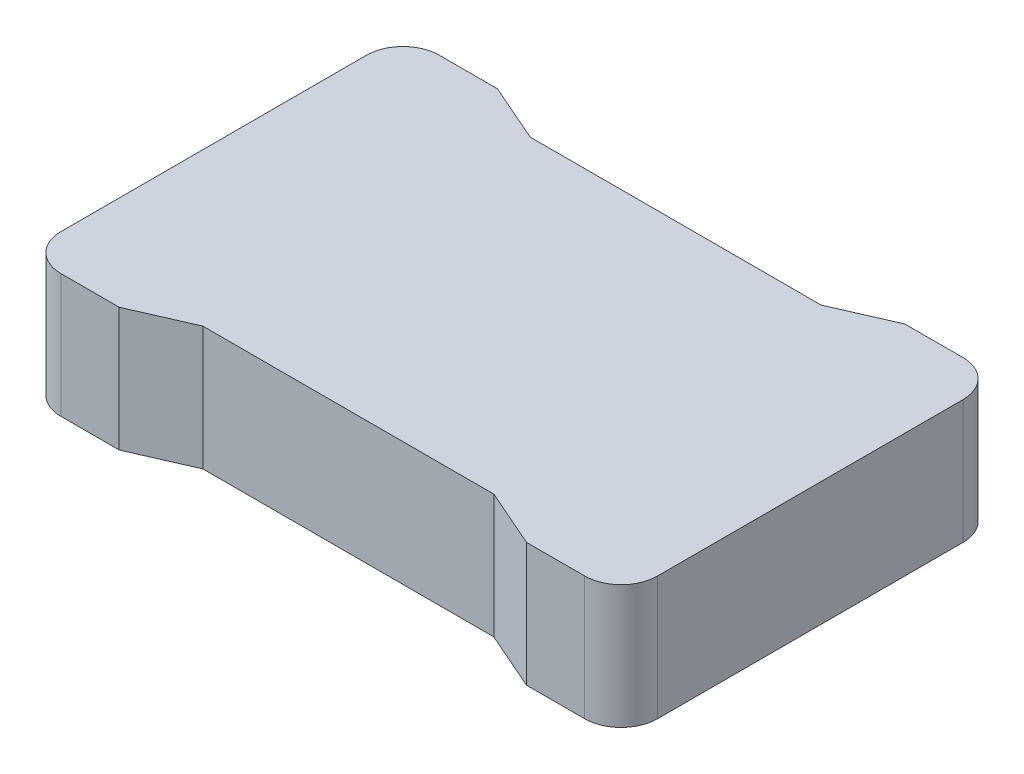
SolidWorks part; units mm, degrees
ref_plane "前基準面" through (0, 0, 0) normal (0, 0, 1) x (1, 0, 0)
ref_plane "上基準面" through (0, 0, 0) normal (0, 1, 0) x (1, 0, 0)
ref_plane "右基準面" through (0, 0, 0) normal (1, 0, 0) x (0, 0, -1)
sketch "草圖1" plane through (0, 0, 0) normal (0, 1, 0) x (1, 0, 0)
  line L0 (28, 26) -> (36, 26)
  line L1 (-36, -26) -> (-28, -26)
  line L2 (-41, -21) -> (-41, 21)
  line L3 (-36, 26) -> (-28, 26)
  line L4 (41, -21) -> (41, 21)
  line L5 (-41, -26) -> (41, 26) construction
  line L6 (-41, 26) -> (41, -26) construction
  line L7 (-20, -22.5) -> (20, -22.5)
  line L8 (-20, -22.5) -> (-20, 22.5) construction
  line L9 (-20, 22.5) -> (20, 22.5)
  line L10 (20, -22.5) -> (20, 22.5) construction
  line L11 (-20, -22.5) -> (20, 22.5) construction
  line L12 (-20, 22.5) -> (20, -22.5) construction
  line L13 (-28, -26) -> (28, -26) construction
  line L14 (-28, -26) -> (-28, 26) construction
  line L15 (-28, 26) -> (28, 26) construction
  line L16 (28, -26) -> (28, 26) construction
  line L17 (-28, -26) -> (28, 26) construction
  line L18 (-28, 26) -> (28, -26) construction
  line L19 (28, -26) -> (36, -26)
  line L20 (-28, 26) -> (-20, 22.5)
  line L21 (20, 22.5) -> (28, 26)
  line L22 (28, -26) -> (20, -22.5)
  line L23 (-20, -22.5) -> (-28, -26)
  arc A0 (36, -26) -> (41, -21) centre (36, -21) ccw
  arc A1 (36, 26) -> (41, 21) centre (36, 21) cw
  arc A2 (-36, -26) -> (-41, -21) centre (-36, -21) cw
  arc A3 (-41, 21) -> (-36, 26) centre (-36, 21) cw
  point P0 (0, 0)
  point P6 (0, 0)
  point P11 (0, 0)
  point P16 (-29.4708, 26)
  point P29 (0, 0)
  point P30 (0, 0)
  point P31 (0, 0)
  dimension "D6" = 5
  dimension "D1" = 40
  dimension "D2" = 52
  dimension "D3" = 82
  dimension "D4" = 45
  dimension "D5" = 56
extrude "填料-伸長1" add sketch "草圖1" along normal blind 17
sketch "草圖2" plane through (0, 0, -22.5) normal (0, 0, -1) x (-1, 0, 0)
  line L0 (41, 17) -> (41, 0) construction
  line L5 (14.85, 8.5) -> (10.15, 8.5) construction
  line L6 (14.85, 6.6) -> (10.15, 6.6)
  line L7 (14.85, 10.4) -> (10.15, 10.4)
  arc A0 (14.85, 6.6) -> (14.85, 10.4) centre (14.85, 8.5) ccw
  arc A1 (10.15, 10.4) -> (10.15, 6.6) centre (10.15, 8.5) ccw
  point P0 (12.5, 8.5)
  point P3 (12.5, 8.5)
  point P10 (0, 0)
  point P11 (41, 8.5)
  dimension "D3" = 4.7
  dimension "D1" = 28.5
  dimension "D2" = 3.8
extrude "除料-伸長1" cut sketch "草圖2" against normal blind 10
